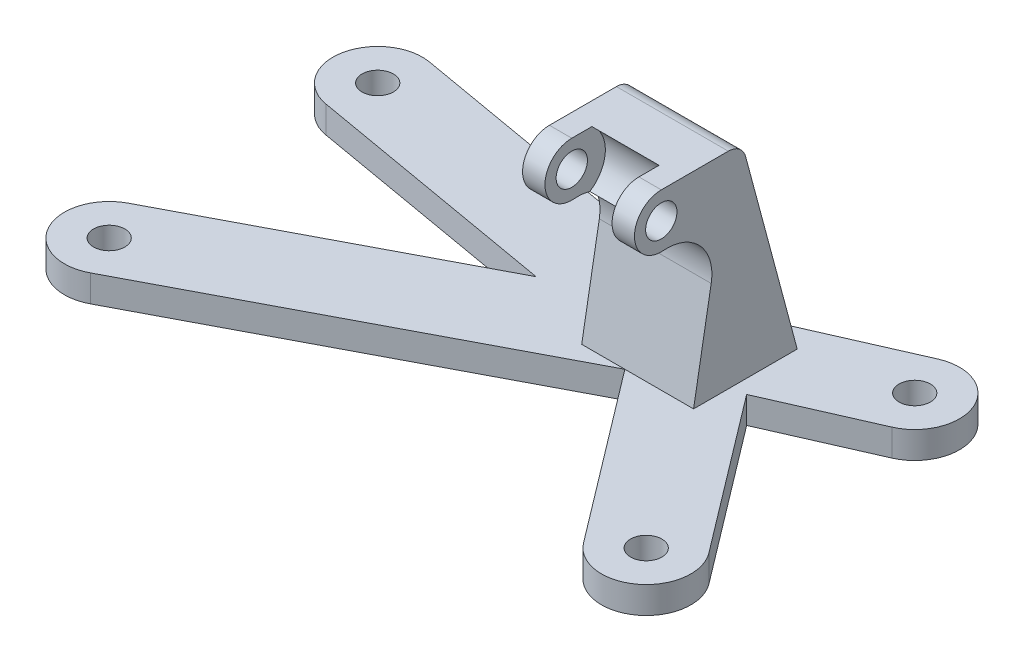
SolidWorks part; units mm, degrees
ref_plane "Front Plane" through (0, 0, 0) normal (0, 0, 1) x (1, 0, 0)
ref_plane "Top Plane" through (0, 0, 0) normal (0, 1, 0) x (1, 0, 0)
ref_plane "Right Plane" through (0, 0, 0) normal (1, 0, 0) x (0, 0, -1)
sketch "Sketch1" plane through (0, 0, 0) normal (0, 1, 0) x (1, 0, 0)
  line L3 (-45.257, -18.0713) -> (-15.3434, -2.3955)
  line L6 (-40.6154, -26.9287) -> (-1.4271, -6.3928)
  line L13 (-43.7966, 2.5746) -> (-15.3434, -2.3955)
  line L14 (-42.0758, 12.4254) -> (-0.6284, 5.1855)
  line L17 (21.0477, -19.4786) -> (7.813, -2.0276)
  line L18 (13.0799, -25.5214) -> (-1.4271, -6.3928)
  line L21 (15.0519, 12.0774) -> (-0.6284, 5.1855)
  line L22 (19.0757, 2.9226) -> (7.813, -2.0276)
  line L24 (-42.9362, 7.5) -> (-42.9362, -22.5) construction
  line L25 (-42.9362, -22.5) -> (17.0638, -22.5) construction
  line L26 (17.0638, -22.5) -> (17.0638, 7.5) construction
  line L27 (17.0638, 7.5) -> (-42.9362, 7.5) construction
  line L28 (-42.9362, 7.5) -> (0, 0) construction
  line L29 (0, 0) -> (17.0638, 7.5) construction
  line L30 (-42.9362, -22.5) -> (0, 0) construction
  line L31 (0, 0) -> (17.0638, -22.5) construction
  line L32 (-12.9362, 7.5) -> (-12.9362, -22.5) construction
  arc A8 (-42.0758, 12.4254) -> (-43.7966, 2.5746) centre (-42.9362, 7.5) ccw
  arc A9 (19.0757, 2.9226) -> (15.0519, 12.0774) centre (17.0638, 7.5) ccw
  arc A10 (-45.257, -18.0713) -> (-40.6154, -26.9287) centre (-42.9362, -22.5) ccw
  arc A11 (13.0799, -25.5214) -> (21.0477, -19.4786) centre (17.0638, -22.5) ccw
  circle A12 centre (-42.9362, -22.5) radius 1.75
  circle A13 centre (-42.9362, 7.5) radius 1.75
  circle A14 centre (17.0638, 7.5) radius 1.75
  circle A15 centre (17.0638, -22.5) radius 1.75
  dimension "D1" = 60
  dimension "D3" = 3.5
  dimension "D4" = 10
  dimension "D2" = 30
  dimension "D5" = 7.5
  dimension "D6" = 12.9362
extrude "Boss-Extrude1" add sketch "Sketch1" along normal blind 3
sketch "Sketch2" plane through (0, 0, 0) normal (1, 0, 0) x (0, 0, -1)
  line L0 (-6.3928, 3) -> (-4.4253, 14.1583)
  line L1 (-19.4786, 3) -> (-2.0276, 3) construction
  line L2 (-10, 26) -> (-2.512, 26)
  line L3 (-0.5802, 24.5176) -> (5.1855, 3)
  line L4 (12.5, 3) -> (2.9226, 3) construction
  line L5 (5.1855, 3) -> (-6.3928, 3)
  line L6 (0, 0) -> (0, 3) construction
  arc A0 (-4.4253, 14.1583) -> (-9.756, 20.0099) centre (-9.3493, 15.0265) ccw
  arc A1 (-9.756, 20.0099) -> (-10, 26) centre (-10, 23) cw
  arc A2 (-0.5802, 24.5176) -> (-2.512, 26) centre (-2.512, 24) ccw
  circle A3 centre (-10, 23) radius 1.75
  point P8 (0, 0)
  dimension "D1" = 20
  dimension "D2" = 3
  dimension "D3" = 3.5
  dimension "D6" = 5
  dimension "D8" = 2
  dimension "D4" = 10
  dimension "D5" = 10
  dimension "D7" = 15
extrude "Boss-Extrude2" add sketch "Sketch2" along normal mid plane 12.5
sketch "Sketch3" plane through (0, 0, 0) normal (1, 0, 0) x (0, 0, -1)
  circle A0 centre (-10, 23) radius 3.75
  arc A1 (-10, 26) -> (-9.756, 20.0099) centre (-10, 23) ccw construction
  dimension "D1" = 7.5
extrude "Cut-Extrude1" cut sketch "Sketch3" against normal mid plane 7.5
